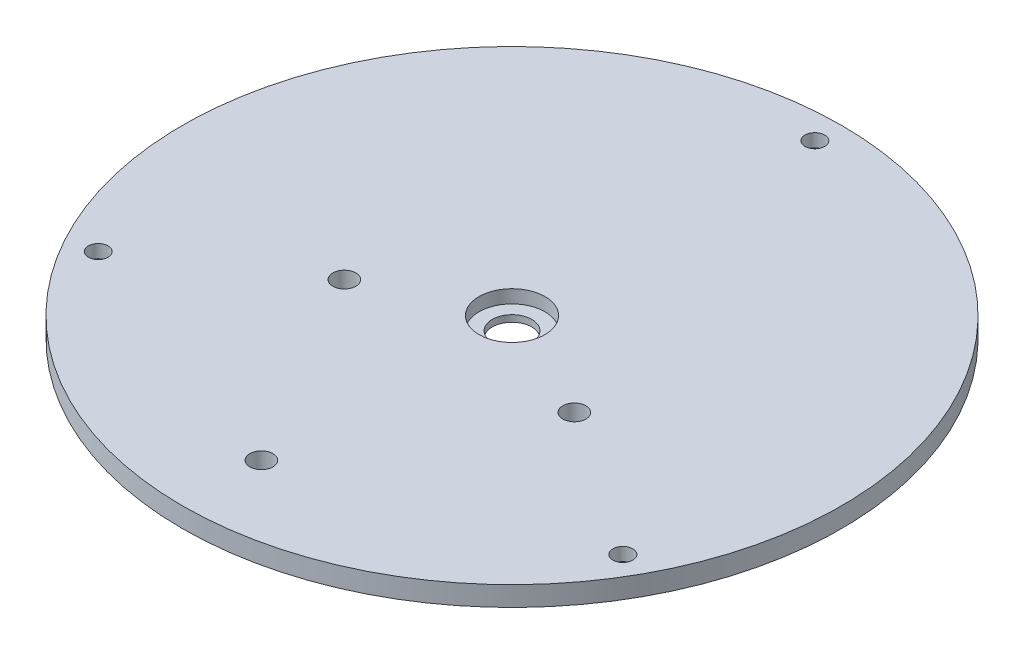
SolidWorks part; units mm, degrees
ref_plane "Front Plane" through (0, 0, 0) normal (0, 0, 1) x (1, 0, 0)
ref_plane "Top Plane" through (0, 0, 0) normal (0, 1, 0) x (1, 0, 0)
ref_plane "Right Plane" through (0, 0, 0) normal (1, 0, 0) x (0, 0, -1)
sketch "Sketch1" plane through (0, 0, 0) normal (0, 1, 0) x (1, 0, 0)
  line L0 (0, 0) -> (109.8419, 0) construction
  line L1 (0, 0) -> (0, 55.6859) construction
  line L2 (0, 0) -> (-60.9364, -35.1816) construction
  line L3 (0, 0) -> (-68.6273, -31.42) construction
  circle A0 centre (0, 0) radius 50
  circle A1 centre (0, 0) radius 3
  circle A2 centre (-39.8, -22.9785) radius 1.5
  circle A3 centre (-17.45, -7.9892) radius 1.75
  circle A4 centre (0, 45.95) radius 1.5
  circle A5 centre (0, -38.0178) radius 1.75
  circle A6 centre (39.8, -22.9785) radius 1.5
  circle A7 centre (17.45, -7.9892) radius 1.75
  dimension "D1" = 100
  dimension "D2" = 6
  dimension "D5" = 3
  dimension "D7" = 3.5
  dimension "D9" = 3
  dimension "D11" = 3.5
  dimension "D3" = 30
  dimension "D4" = 24.6
  dimension "D6" = 39.8
  dimension "D8" = 17.45
  dimension "D10" = 45.95
  dimension "D12" = 38.0178
extrude "Boss-Extrude1" add sketch "Sketch1" along normal blind 3
sketch "Sketch2" plane through (0, 3, 0) normal (0, 1, 0) x (1, 0, 0)
  circle A0 centre (0, 0) radius 5
  dimension "D1" = 10
extrude "Cut-Extrude1" cut sketch "Sketch2" against normal blind 2
chamfer "Chamfer1" distance 1 angle 45 3 edges at (0, 0, -44.45) (-39.8, 0, 24.4785) (39.8, 0, 21.4785)
